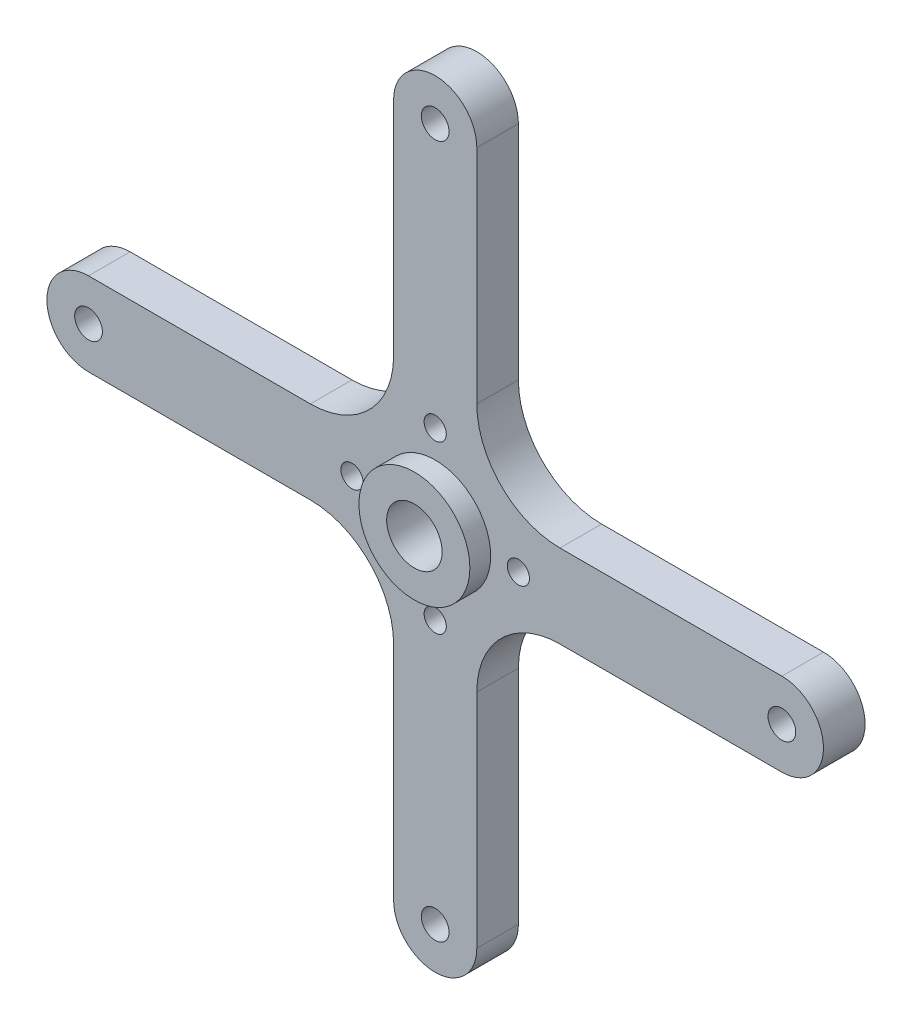
SolidWorks part; units mm, degrees
ref_plane "Front Plane" through (0, 0, 0) normal (0, 0, 1) x (1, 0, 0)
ref_plane "Top Plane" through (0, 0, 0) normal (0, 1, 0) x (1, 0, 0)
ref_plane "Right Plane" through (0, 0, 0) normal (1, 0, 0) x (0, 0, -1)
sketch "Sketch1" plane through (0, 0, 0) normal (0, 0, 1) x (1, 0, 0)
  line L0 (6, 0) -> (-6, 0)
  line L1 (25, 0) -> (-25, 0) construction
  line L2 (25, -3) -> (-25, -3)
  line L3 (25, 3) -> (-25, 3)
  line L4 (0, -25) -> (0, 25) construction
  line L5 (-3, -25) -> (-3, 25)
  line L6 (3, -25) -> (3, 25)
  line L7 (0, 6) -> (0, -6)
  circle A0 centre (-6, 0) radius 0.8
  circle A1 centre (6, 0) radius 0.8
  arc A2 (25, -3) -> (25, 3) centre (25, 0) ccw
  arc A3 (-25, 3) -> (-25, -3) centre (-25, 0) ccw
  arc A4 (-3, -25) -> (3, -25) centre (0, -25) ccw
  arc A5 (3, 25) -> (-3, 25) centre (0, 25) ccw
  circle A6 centre (0, 6) radius 0.8
  circle A7 centre (0, -6) radius 0.8
  point P4 (0, 0)
  point P9 (0, 0)
  point P15 (0, 0)
  point P24 (0, 8.7103)
  point P25 (0, 0)
  dimension "D1" = 1.6
  dimension "D3" = 1.6
  dimension "D5" = 3
  dimension "D7" = 3
  dimension "D8" = 1.6
  dimension "D9" = 1.6
  dimension "D2" = 12
  dimension "D4" = 50
  dimension "D6" = 50
  dimension "D10" = 12
extrude "Boss-Extrude1" add sketch "Sketch1" along normal blind 3
fillet "Fillet1" radius 6 4 edges at (-3, 3, 1.5) (-3, -3, 1.5) (3, -3, 1.5) (3, 3, 1.5)
sketch "Sketch2" plane through (0, 0, 3) normal (0, 0, 1) x (1, 0, 0)
  circle A0 centre (0, 0) radius 2
  dimension "D1" = 4
extrude "Cut-Extrude1" cut sketch "Sketch2" against normal blind 3
sketch "Sketch3" plane through (0, 0, 3) normal (0, 0, 1) x (1, 0, 0)
  circle A0 centre (0, 0) radius 4
  circle A1 centre (0, 0) radius 2
  dimension "D1" = 8
  dimension "D2" = 4
extrude "Boss-Extrude2" add sketch "Sketch3" along normal blind 1.5
sketch "Sketch4" plane through (0, 0, 3) normal (0, 0, 1) x (1, 0, 0)
  circle A0 centre (0, 25) radius 1
  circle A1 centre (25, 0) radius 1
  circle A2 centre (0, -25) radius 1
  circle A3 centre (-25, 0) radius 1
  point P3 (29.9195, -3)
  point P12 (0, 0)
  dimension "D1" = 2
  dimension "D2" = 4
extrude "Cut-Extrude2" cut sketch "Sketch4" against normal up to vertex (3 mm away) up to point (0, 0, 0)
